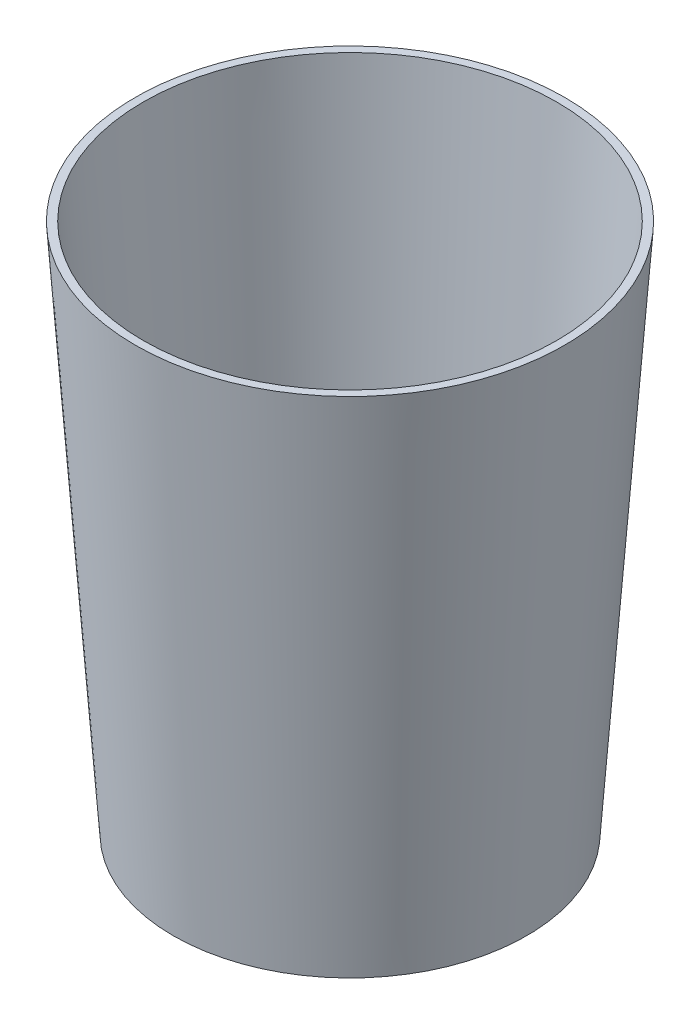
SolidWorks part; units mm, degrees
ref_plane "Front Plane" through (0, 0, 0) normal (0, 0, 1) x (1, 0, 0)
ref_plane "Top Plane" through (0, 0, 0) normal (0, 1, 0) x (1, 0, 0)
ref_plane "Right Plane" through (0, 0, 0) normal (1, 0, 0) x (0, 0, -1)
sketch "Sketch2" plane through (0, 0, 0) normal (0, 1, 0) x (1, 0, 0)
  circle A0 centre (0, 0) radius 88.9
  dimension "D1" = 177.8
sketch3d "3DSketch1"
  circle A1 centre (0, 266.7, 0) radius 107.95
  point P2 (0, 374.65, 0)
  dimension "D2" = 215.9
  dimension "D1" = 266.7
sketch "Sketch3" plane through (0, 0, 0) normal (0, 0, 1) x (1, 0, 0)
  line L0 (-88.9, 0) -> (-107.95, 266.7)
  line L1 (88.9, 0) -> (-88.9, 0) construction
  line L2 (107.95, 266.7) -> (-107.95, 266.7) construction
  line L3 (88.9, 0) -> (107.95, 266.7)
sketch "Sketch7" plane through (0, 0, 0) normal (0, 0, 1) x (1, 0, 0)
  line L0 (0, 0) -> (0, 266.7)
  line L1 (0, 266.7) -> (107.95, 266.7)
  line L2 (107.95, 266.7) -> (88.9, 0)
  line L3 (88.9, 0) -> (0, 0)
revolve "Revolve1" add sketch "Sketch7" angle 360 about L0
shell "Shell1" thickness 4
